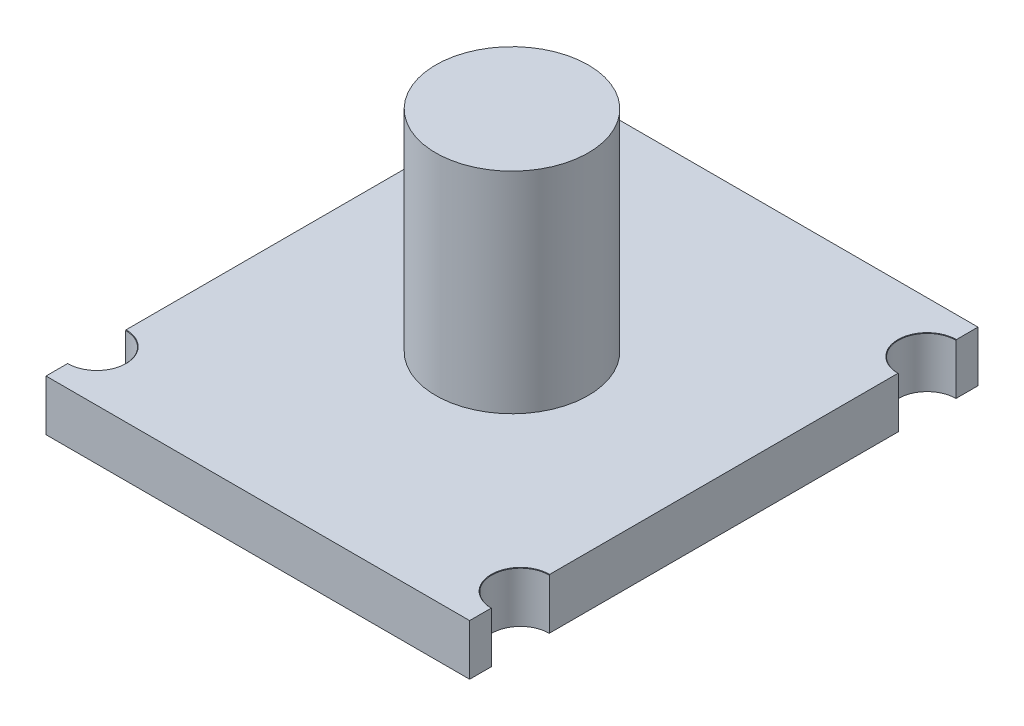
SolidWorks part; units mm, degrees
ref_plane "Front Plane" through (0, 0, 0) normal (0, 0, 1) x (1, 0, 0)
ref_plane "Top Plane" through (0, 0, 0) normal (0, 1, 0) x (1, 0, 0)
ref_plane "Right Plane" through (0, 0, 0) normal (1, 0, 0) x (0, 0, -1)
sketch "Sketch1" plane through (0, 0, 0) normal (0, 1, 0) x (1, 0, 0)
  line L1 (0, 0) -> (25, 0)
  line L2 (0, 0) -> (0, 30)
  line L3 (0, 30) -> (25, 30)
  line L4 (25, 0) -> (25, 30)
  dimension "D1" = 30
  dimension "D2" = 25
extrude "Boss-Extrude1" add sketch "Sketch1" along normal blind 3
hole_wizard "M3 Clearance Hole1" positions "Sketch2" profile "Sketch3" hole size "M3" standard "ANSI Metric" end condition through all
sketch "Sketch2" plane through (0, 3, 0) normal (0, 1, 0) x (1, 0, 0)
  line L0 (0, 30) -> (0, 0) construction
  line L1 (12.5, 0) -> (12.5, 30) construction
  line L2 (0, 0) -> (25, 0) construction
  line L3 (25, 30) -> (0, 30) construction
  line L5 (25, 15) -> (0, 15) construction
  line L6 (25, 0) -> (25, 30) construction
  point P0 (0, 3)
  point P20 (0, 27)
  point P21 (25, 3)
  point P22 (25, 27)
  dimension "D1" = 3
sketch "Sketch3" plane through (0, 3, -3) normal (1, 0, 0) x (0, 0, 1)
  line L0 (0, 0) -> (0, 3)
  line L1 (0, 3) -> (1.7, 3)
  line L2 (1.7, 3) -> (1.7, 0.025)
  line L3 (1.7, 0.025) -> (1.725, 0)
  line L5 (1.725, 0) -> (0, 0)
  line L6 (-1.7, 0.025) -> (-1.725, 0) construction
  line L11 (0, -6.35) -> (0, 107.95) construction
  dimension "Thru Hole Dia." = 3.4
  dimension "Thru Hole Depth" = 3
  dimension "Near C'Sink Dia." = 3.45
  dimension "Near C'Sink Angle" = 90
sketch "Sketch4" plane through (0, 3, 0) normal (0, 1, 0) x (1, 0, 0)
  line L0 (12.5, 0) -> (12.5, 30) construction
  line L1 (0, 0) -> (25, 0) construction
  line L2 (25, 30) -> (0, 30) construction
  line L3 (0, 15) -> (25, 15) construction
  line L4 (0, 25.275) -> (0, 4.725) construction
  line L5 (25, 4.725) -> (25, 25.275) construction
  circle A0 centre (12.5, 15) radius 4.5
  dimension "D1" = 9
extrude "Boss-Extrude2" add sketch "Sketch4" along normal blind 12.4
sketch "Sketch5" plane through (0, 0, 0) normal (0, -1, 0) x (1, 0, 0)
  line L0 (0, -25.3) -> (0, -4.7) construction
  line L1 (0, -9) -> (6, -9)
  line L2 (0, -9) -> (0, -21)
  line L3 (0, -21) -> (6, -21)
  line L4 (6, -9) -> (6, -21)
  point P6 (0, -15)
  dimension "D1" = 12
  dimension "D2" = 6
extrude "Boss-Extrude3" add sketch "Sketch5" along normal blind 6
